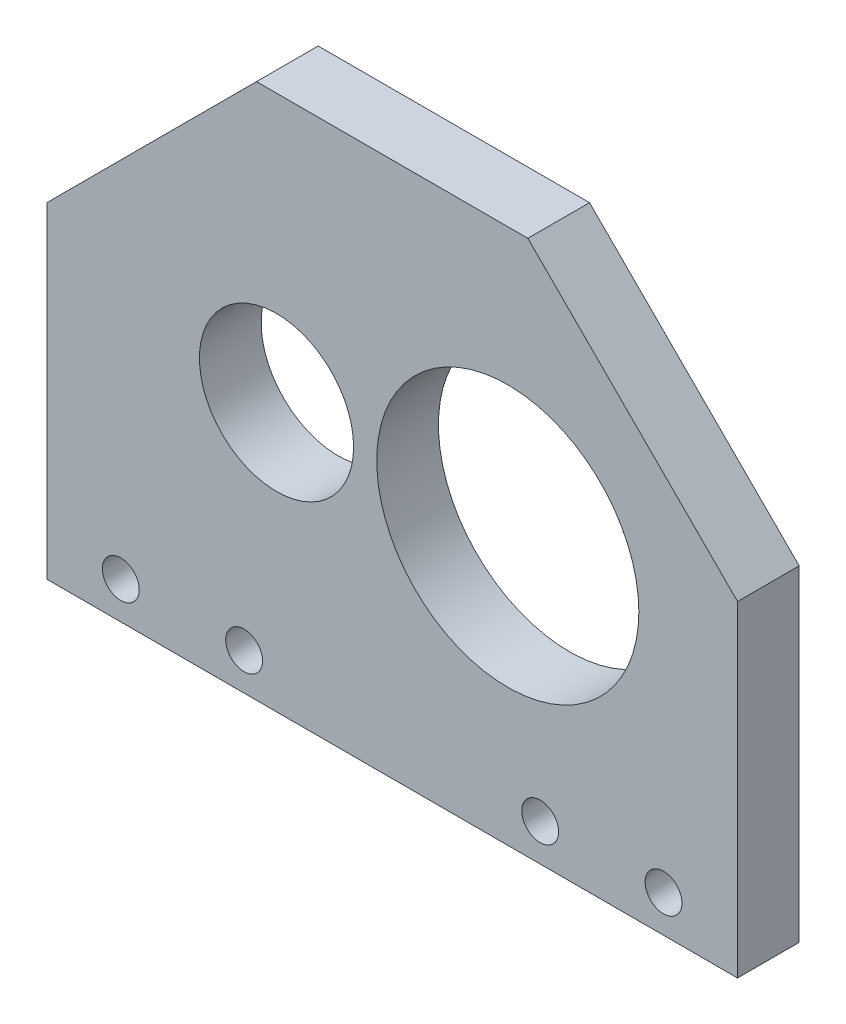
SolidWorks part; units mm, degrees
ref_plane "Front Plane" through (0, 0, 0) normal (0, 0, 1) x (1, 0, 0)
ref_plane "Top Plane" through (0, 0, 0) normal (0, 1, 0) x (1, 0, 0)
ref_plane "Right Plane" through (0, 0, 0) normal (1, 0, 0) x (0, 0, -1)
sketch "Sketch1" plane through (0, 0, 0) normal (0, 0, 1) x (1, 0, 0)
  line L1 (35.56, -27.5819) -> (-35.56, -27.5819)
  line L2 (35.56, -27.5819) -> (35.56, 27.5819)
  line L3 (35.56, 27.5819) -> (-35.56, 27.5819)
  line L4 (-35.56, -27.5819) -> (-35.56, 27.5819)
  line L5 (35.56, -27.5819) -> (-35.56, 27.5819) construction
  line L6 (35.56, 27.5819) -> (-35.56, -27.5819) construction
  circle A0 centre (11.9062, 0) radius 13.4937
  circle A1 centre (-11.9062, 0) radius 7.9375
  point P0 (0, 0)
  dimension "D3" = 26.9875
  dimension "D6" = 15.875
  dimension "D1" = 71.12
  dimension "D2" = 55.1637
  dimension "D4" = 0
  dimension "D5" = 0
  dimension "D7" = 11.9062
  dimension "D8" = 11.9062
extrude "Boss-Extrude1" add sketch "Sketch1" along normal blind 6.35
hole_wizard "#6 Clearance Hole1" positions "Sketch2" profile "Sketch3" hole size "#6" standard "ANSI Inch" end condition through all
sketch "Sketch2" plane through (0, 0, 6.35) normal (0, 0, 1) x (1, 0, 0)
  line L1 (-27.94, -23.7719) -> (-15.24, -23.7719)
  line L3 (15.24, -23.7719) -> (27.94, -23.7719)
  line L5 (-35.56, -27.5819) -> (35.56, -27.5819) construction
  line L6 (-35.56, 27.5819) -> (-35.56, -27.5819) construction
  line L7 (35.56, -27.5819) -> (35.56, 27.5819) construction
  point P0 (-27.94, -23.7719)
  point P2 (-15.24, -23.7719)
  point P4 (15.24, -23.7719)
  point P6 (27.94, -23.7719)
  dimension "D1" = 12.7
  dimension "D2" = 12.7
  dimension "D3" = 3.81
  dimension "D4" = 3.81
  dimension "D5" = 7.62
  dimension "D6" = 7.62
sketch "Sketch3" plane through (-27.94, -23.7719, 6.35) normal (1, 0, 0) x (0, -1, 0)
  line L0 (0, 0) -> (0, 6.35)
  line L1 (0, 6.35) -> (1.8986, 6.35)
  line L2 (1.8986, 6.35) -> (1.8986, 0)
  line L5 (1.8986, 0) -> (0, 0)
  line L11 (0, -6.35) -> (0, 107.95) construction
  dimension "Thru Hole Dia." = 3.7973
  dimension "Thru Hole Depth" = 6.35
sketch "Sketch4" plane through (0, 0, 6.35) normal (0, 0, 1) x (1, 0, 0)
  line L0 (-35.56, 5.9919) -> (-13.97, 27.5819)
  line L1 (-35.56, 27.5819) -> (-35.56, -27.5819) construction
  line L2 (35.56, 27.5819) -> (-35.56, 27.5819) construction
  line L3 (35.56, 5.9919) -> (13.97, 27.5819)
  line L4 (35.56, -27.5819) -> (35.56, 27.5819) construction
  line L5 (-35.56, 27.5819) -> (-35.56, 5.9919)
  line L6 (-13.97, 27.5819) -> (-35.56, 27.5819)
  line L7 (13.97, 27.5819) -> (35.56, 27.5819)
  line L8 (35.56, 27.5819) -> (35.56, 5.9919)
  dimension "D1" = 21.59
  dimension "D2" = 21.59
  dimension "D3" = 21.59
  dimension "D4" = 21.59
extrude "Cut-Extrude1" cut sketch "Sketch4" against normal through all
